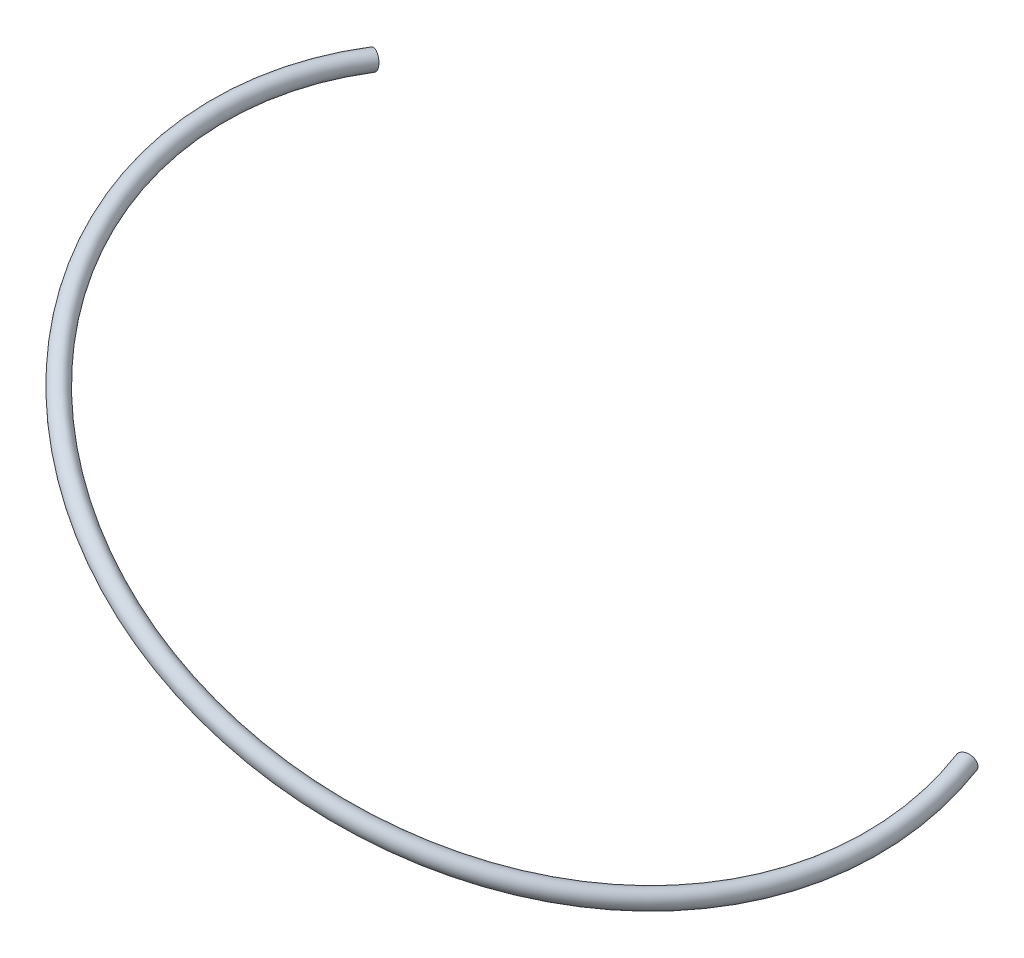
SolidWorks part; units mm, degrees
material "PVC 0.007 Plasticized"
ref_plane "Front Plane" through (0, 0, 0) normal (0, 0, 1) x (1, 0, 0)
ref_plane "Top Plane" through (0, 0, 0) normal (0, 1, 0) x (1, 0, 0)
ref_plane "Right Plane" through (0, 0, 0) normal (1, 0, 0) x (0, 0, -1)
sketch3d "3DSketch1"
  line L1 (105, 25.85, 6.25) -> (105, 25.85, 22.25) construction
  circle A0 centre (240.75, -38.2, 27) radius 3.5 construction
  circle A1 centre (240.75, -38.2, 27) radius 3.5 construction
  point P0 (105, 25.85, 22.25)
  point P2 (105, 25.85, 22.25)
  point P5 (240.75, -38.2, 30.5)
  point P7 (240.75, -38.2, 30.5)
  point P8 (240.75, -38.2, 27)
  point P9 (88.75, 25.85, 22.25)
ref_plane "Plane1" through (29.0945, 61.664, 0) normal (0.4267, 0.9044, 0) x (0.9044, -0.4267, 0)
sketch "Sketch2" plane through (29.0945, 61.664, 0) normal (0.4267, 0.9044, 0) x (0.9044, -0.4267, 0)
  arc A0 (83.9302, -22.25) -> (234.0318, -27) centre (158.1367, -51.3055) ccw
  dimension "D1" = 304.8
sweep "Sweep1" add path "Sketch2" circular profile diameter 4 parameters "D3"=4
